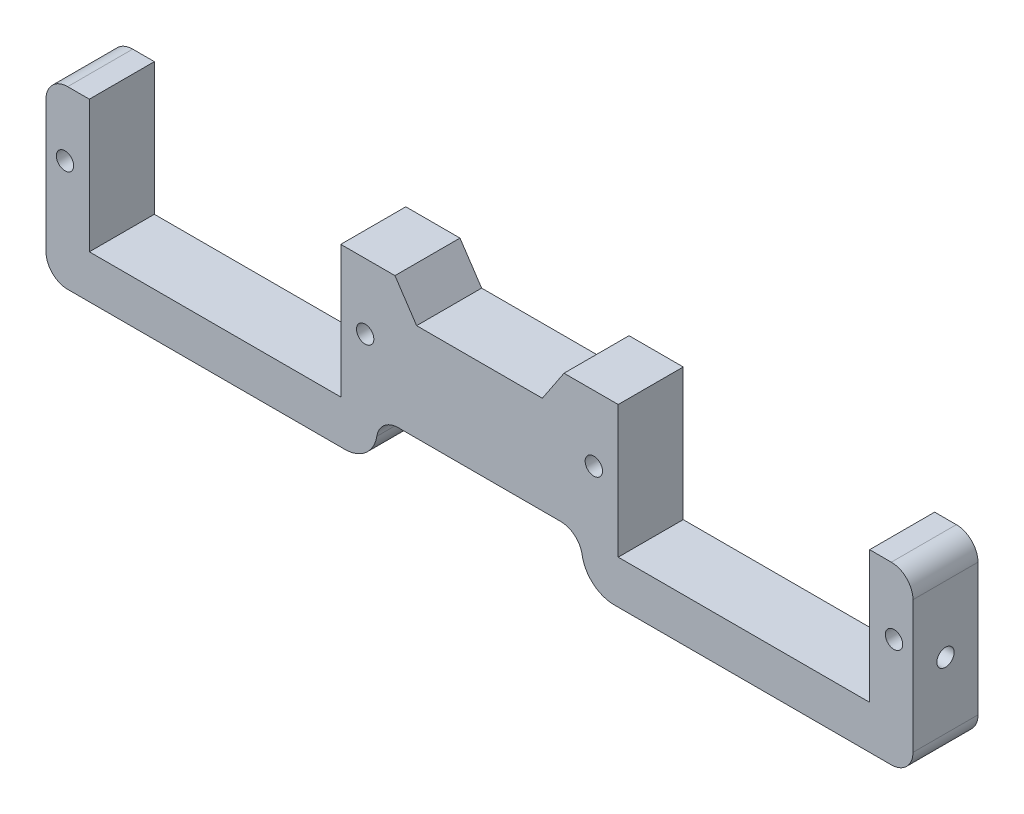
SolidWorks part; units mm, degrees
ref_plane "Ön Düzlem" through (0, 0, 0) normal (0, 0, 1) x (1, 0, 0)
ref_plane "Üst Düzlem" through (0, 0, 0) normal (0, 1, 0) x (1, 0, 0)
ref_plane "Sağ Düzlem" through (0, 0, 0) normal (1, 0, 0) x (0, 0, -1)
sketch "Çizim1" plane through (0, 0, 0) normal (0, 0, 1) x (1, 0, 0)
  line L0 (-40, 0) -> (40, 0) construction
  line L1 (-40, 2) -> (-40, 14.2)
  line L2 (-38, 16.2) -> (-36, 16.2)
  line L3 (-36, 16.2) -> (-36, 4)
  line L4 (-36, 4) -> (-12.8, 4)
  line L5 (-12.8, 4) -> (-12.8, 16.2)
  line L8 (-5.8, 13.1999) -> (5.8, 13.1999)
  line L9 (0, 13.1999) -> (0, 4.1999) construction
  line L10 (7.5, 4.1999) -> (-7.5, 4.1999)
  line L11 (-9.5, 2.1999) -> (-9.5, 0)
  line L12 (-9.5, 0) -> (-38, 0)
  line L13 (9.5, 0) -> (38, 0)
  line L14 (9.5, 2.1999) -> (9.5, 0)
  line L16 (12.8, 16.2) -> (11, 16.2)
  line L17 (12.8, 4) -> (12.8, 16.2)
  line L18 (36, 4) -> (12.8, 4)
  line L19 (36, 16.2) -> (36, 4)
  line L20 (38, 16.2) -> (36, 16.2)
  line L21 (40, 2) -> (40, 14.2)
  line L22 (-38.25, 16.2499) -> (-38.25, 10.1499) construction
  line L23 (-10.55, 16) -> (-10.55, 10.1499) construction
  line L24 (-12.8, 16.2) -> (-7.8, 16.2)
  line L25 (11, 16.2) -> (7.8, 16.2)
  line L26 (7.8, 16.2) -> (5.8, 13.1999)
  line L28 (-7.8, 16.2) -> (-5.8, 13.1999)
  line L30 (-38.25, 10.1499) -> (-10.55, 10.1499) construction
  line L31 (-10.55, 10.1499) -> (10.55, 10.1499) construction
  line L33 (-24.4, 10.1499) -> (-24.4, 4) construction
  line L34 (10.55, 10.1499) -> (38.25, 10.1499) construction
  circle A0 centre (-10.55, 10.1499) radius 0.8
  circle A1 centre (-38.25, 10.1499) radius 0.8
  circle A2 centre (38.25, 10.1499) radius 0.8
  circle A3 centre (10.55, 10.1499) radius 0.8
  arc A4 (38, 0) -> (40, 2) centre (38, 2) ccw
  arc A5 (38, 16.2) -> (40, 14.2) centre (38, 14.2) cw
  arc A8 (-40, 14.2) -> (-38, 16.2) centre (-38, 14.2) cw
  arc A9 (-40, 2) -> (-38, 0) centre (-38, 2) ccw
  arc A10 (9.5, 2.1999) -> (7.5, 4.1999) centre (7.5, 2.1999) ccw
  arc A11 (-7.5, 4.1999) -> (-9.5, 2.1999) centre (-7.5, 2.1999) ccw
  point P4 (0, 0)
  point P40 (40, 16.2)
  point P43 (7.8, 16.2)
  point P46 (-7.8, 16.2)
  point P49 (-40, 16.2)
  point P55 (9.5, 4.1999)
  point P58 (-9.5, 4.1999)
  point P61 (9, 12.9999)
  point P64 (-9, 12.9999)
  dimension "D9" = 1.6
  dimension "D10" = 2
  dimension "D11" = 27.7
  dimension "D2" = 23.2
  dimension "D3" = 4
  dimension "D4" = 5
  dimension "D5" = 9
  dimension "D6" = 12.2
  dimension "D7" = 4
  dimension "D8" = 6.1
extrude "Yükseklik-Ekstrüzyon1" add sketch "Çizim1" along normal mid plane 6
fillet "Radyus1" radius 3 2 edges at (9.5, 0, 0) (-9.5, 0, 0)
sketch "Çizim6" plane through (40, 0, 0) normal (1, 0, 0) x (0, 0, -1)
  line L0 (0, 2) -> (0, 8.1) construction
  line L1 (-3, 2) -> (3, 2) construction
  line L2 (0, 8.1) -> (3, 8.1) construction
  line L3 (3, 2) -> (3, 14.2) construction
  circle A0 centre (0, 8.1) radius 0.8
  dimension "D1" = 1.6
extrude "Kes-Ekstrüzyon5" cut sketch "Çizim6" against normal up to next contours A0
